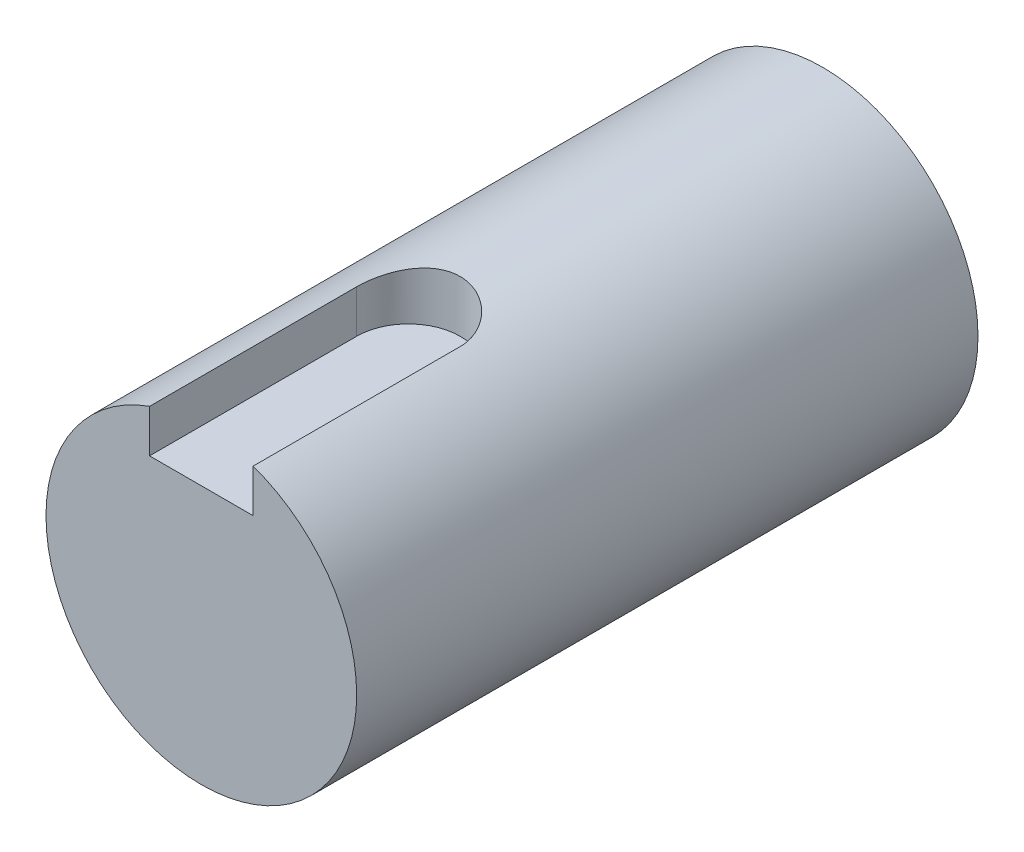
SolidWorks part; units mm, degrees
ref_plane "Front Plane" through (0, 0, 0) normal (0, 0, 1) x (1, 0, 0)
ref_plane "Top Plane" through (0, 0, 0) normal (0, 1, 0) x (1, 0, 0)
ref_plane "Right Plane" through (0, 0, 0) normal (1, 0, 0) x (0, 0, -1)
sketch "Sketch1" plane through (0, 0, 0) normal (0, 0, 1) x (1, 0, 0)
  circle A0 centre (0, 0) radius 15
  dimension "D1" = 30
extrude "Boss-Extrude1" add sketch "Sketch1" along normal mid plane 60
ref_plane "Plane1" through (0, 15, 0) normal (0, 1, 0) x (1, 0, 0)
sketch "Sketch2" plane through (0, 15, 0) normal (0, 1, 0) x (1, 0, 0)
  line L0 (0, -10) -> (0, -30) construction
  line L1 (0, -16.5) -> (0, 16.5) construction
  line L2 (5, -10) -> (5, -30)
  line L3 (-5, -10) -> (-5, -30)
  line L4 (-15, -30) -> (15, -30) construction
  arc A0 (5, -10) -> (-5, -10) centre (0, -10) ccw
  arc A1 (-5, -30) -> (5, -30) centre (0, -30) ccw
  point P5 (0, -20)
  point P10 (0, -5)
  point P11 (0, 0)
  point P12 (0, 0)
  dimension "D1" = 10
  dimension "D2" = 25
extrude "Cut-Extrude1" cut sketch "Sketch2" against normal blind 5
